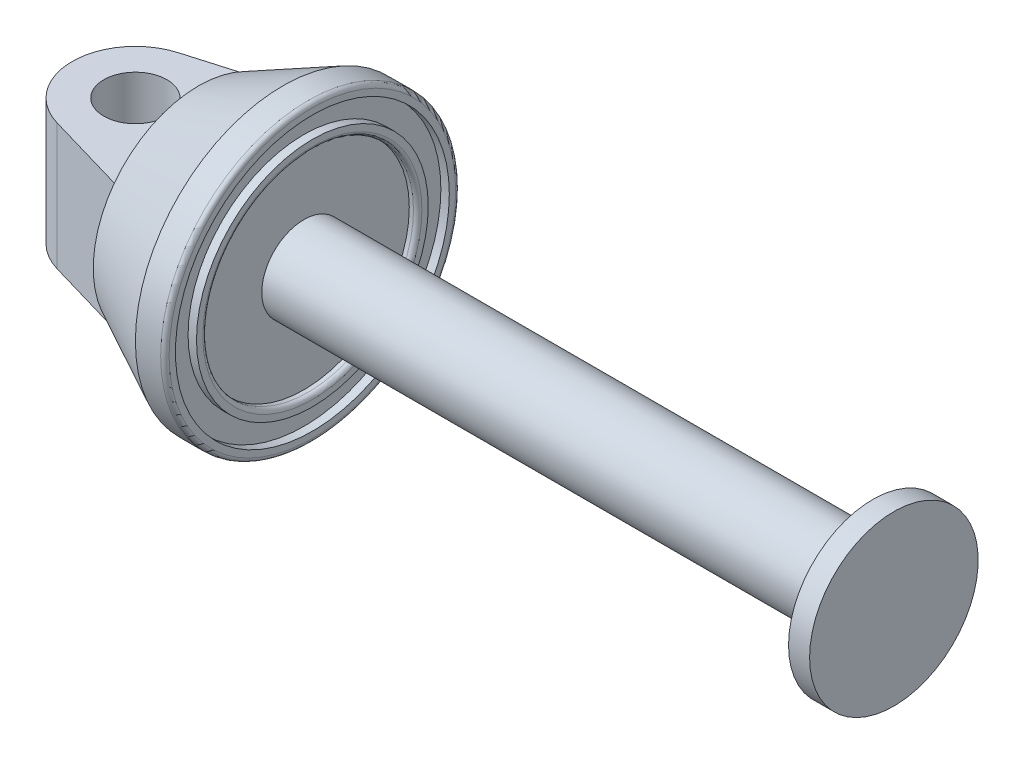
SolidWorks part; units mm, degrees
material "1060 Alloy"
ref_plane "Front Plane" through (0, 0, 0) normal (0, 0, 1) x (1, 0, 0)
ref_plane "Top Plane" through (0, 0, 0) normal (0, 1, 0) x (1, 0, 0)
ref_plane "Right Plane" through (0, 0, 0) normal (1, 0, 0) x (0, 0, -1)
sketch "Sketch1" plane through (0, 0, 0) normal (0, 1, 0) x (1, 0, 0)
  line L0 (-36.25, 17.5) -> (-33.75, 17.5)
  line L1 (-33.75, 17.5) -> (-33.75, 5)
  line L2 (-33.75, 5) -> (33.75, 5)
  line L3 (33.75, 5) -> (33.75, 10)
  line L4 (33.75, 10) -> (36.25, 10)
  line L5 (36.25, 10) -> (36.25, 0)
  line L8 (-36.25, 0) -> (36.25, 0)
  line L9 (-36.25, 17.5) -> (-46.25, 12.5)
  line L10 (-46.25, 12.5) -> (-46.25, 0)
  line L11 (-46.25, 0) -> (-36.25, 0)
  point P2 (0, 5)
  dimension "D1" = 5
  dimension "D2" = 2.5
  dimension "D3" = 17.5
  dimension "D4" = 67.5
  dimension "D5" = 2.5
  dimension "D6" = 10
  dimension "D7" = 10
  dimension "D8" = 12.5
revolve "Revolve1" add sketch "Sketch1" angle 360 about L8
sketch "Sketch2" plane through (-33.75, 0, 0) normal (1, 0, 0) x (0, 0, -1)
  circle A0 centre (0, 0) radius 12.5
  circle A2 centre (0, 0) radius 13.75
  circle A3 centre (0, 0) radius 16.25
  circle A4 centre (0, 0) radius 16.25
  circle A5 centre (0, 0) radius 17.5
  circle A6 centre (0, 0) radius 17.5 construction
  circle M2 centre (0, 0) radius 17.5
  dimension "D1" = 25
  dimension "D2" = 1.25
  dimension "D3" = 1.25
extrude "Boss-Extrude1" add sketch "Sketch2" along normal blind 1 contours A4 M2 | A2 A0
fillet "Fillet1" radius 0.5 2 edges at (-32.75, 0, -12.5) (-32.75, 0, -17.5)
sketch "Sketch3" plane through (0, 0, 0) normal (0, 1, 0) x (1, 0, 0)
  line L0 (-46.25, 10) -> (-46.25, -10)
  line L1 (-46.25, 12.5) -> (-46.25, -12.5) construction
  line L2 (-46.25, -10) -> (-55.85, -7.2)
  line L4 (-55.85, 7.2) -> (-46.25, 10)
  arc A0 (-55.85, 7.2) -> (-55.85, -7.2) centre (-53.75, 0) ccw
  circle A1 centre (-53.75, 0) radius 3.75
  point P8 (-46.25, 0)
  dimension "D1" = 7.5
  dimension "D4" = 7.5
  dimension "D2" = 7.5
  dimension "D3" = 20
extrude "Boss-Extrude2" add sketch "Sketch3" along normal mid plane 15
